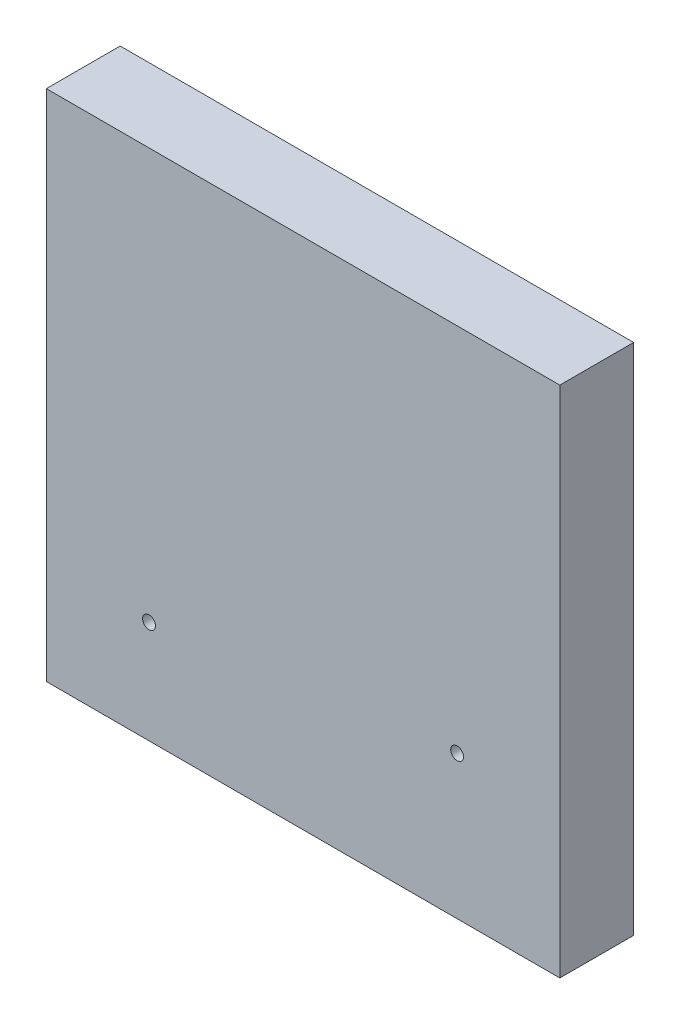
SolidWorks part; units mm, degrees
material "Pine"
ref_plane "Front Plane" through (0, 0, 0) normal (0, 0, 1) x (1, 0, 0)
ref_plane "Top Plane" through (0, 0, 0) normal (0, 1, 0) x (1, 0, 0)
ref_plane "Right Plane" through (0, 0, 0) normal (1, 0, 0) x (0, 0, -1)
sketch "Sketch1" plane through (0, 0, 0) normal (0, 0, 1) x (1, 0, 0)
  line L1 (0, 0) -> (127, 0)
  line L2 (0, 0) -> (0, 127)
  line L3 (0, 127) -> (127, 127)
  line L4 (127, 0) -> (127, 127)
  circle A0 centre (25.4, 25.4) radius 1.5875
  circle A1 centre (101.6, 35.433) radius 1.5875
  dimension "D3" = 3.175
  dimension "D1" = 127
  dimension "D2" = 127
  dimension "D4" = 76.2
  dimension "D5" = 25.4
  dimension "D6" = 25.4
  dimension "D7" = 10.033
extrude "Boss-Extrude1" add sketch "Sketch1" along normal blind 18.2626
